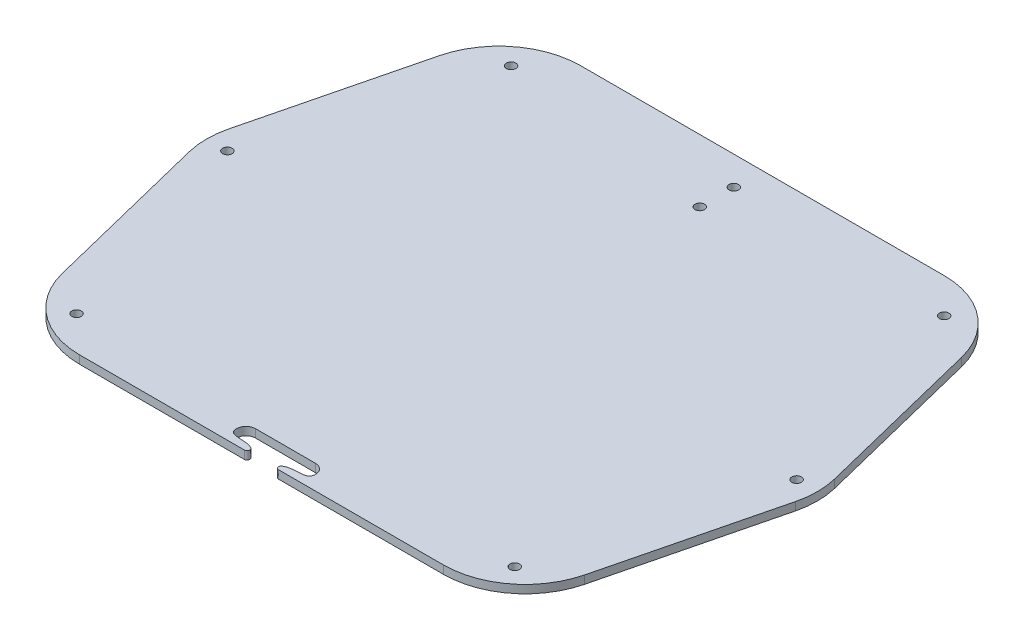
SolidWorks part; units mm, degrees
ref_plane "前视基准面" through (0, 0, 0) normal (0, 0, 1) x (1, 0, 0)
ref_plane "上视基准面" through (0, 0, 0) normal (0, 1, 0) x (1, 0, 0)
ref_plane "右视基准面" through (0, 0, 0) normal (1, 0, 0) x (0, 0, -1)
sketch "草图1" plane through (0, 0, 0) normal (0, 1, 0) x (1, 0, 0)
  line L3 (-66.7806, 154.594) -> (66.7806, 154.594)
  line L4 (-95.8987, 131.8145) -> (-111.2655, 69.8447)
  line L5 (-96.25, 148.3486) -> (-96.25, 83.3486) construction
  line L6 (95.8987, 131.8145) -> (111.2655, 69.8447)
  line L7 (95.8987, -6.5662) -> (111.2655, 55.4037)
  line L9 (-95.8987, -6.5662) -> (-111.2655, 55.4037)
  line L10 (137.9048, 62.6242) -> (-113.2043, 62.6242) construction
  line L12 (-66.7806, -29.3457) -> (66.7806, -29.3457)
  line L20 (0, 9.3997) -> (0, 129.3997) construction
  arc A0 (95.8987, -6.5662) -> (66.7806, -29.3457) centre (66.7806, 0.6543) cw
  arc A1 (-66.7806, -29.3457) -> (-95.8987, -6.5662) centre (-66.7806, 0.6543) cw
  arc A2 (111.2655, 55.4037) -> (111.2655, 69.8447) centre (82.1474, 62.6242) ccw
  arc A3 (-111.2655, 69.8447) -> (-111.2655, 55.4037) centre (-82.1474, 62.6242) ccw
  arc A6 (-66.7806, 154.594) -> (-95.8987, 131.8145) centre (-66.7806, 124.594) ccw
  arc A7 (95.8987, 131.8145) -> (66.7806, 154.594) centre (66.7806, 124.594) ccw
  point P16 (-90.25, 154.594)
  point P18 (90.25, -29.3457)
  point P24 (-90.25, -29.3457)
  point P26 (0, 62.6242)
  point P27 (90.25, 154.594)
  point P28 (113.2043, 62.6242)
  dimension "D5" = 30
  dimension "D6" = 30
extrude "凸台-拉伸1" add sketch "草图1" along normal blind 3
sketch "草图2" plane through (0, 3, 0) normal (0, 1, 0) x (1, 0, 0)
  circle A0 centre (-104.5075, 62.6242) radius 1.75 construction
  circle A1 centre (-80.4502, -16.819) radius 1.75 construction
  circle A2 centre (-104.5075, 62.6242) radius 1.75
  circle A3 centre (-80.4502, -16.819) radius 1.75
  circle A4 centre (104.5075, 62.6242) radius 1.75 construction
  circle A5 centre (80.4502, -16.819) radius 1.75 construction
  circle A6 centre (104.5075, 62.6242) radius 1.75
  circle A7 centre (80.4502, -16.819) radius 1.75
extrude "切除-拉伸1" cut sketch "草图2" against normal blind 10
sketch "草图3" plane through (0, 3, 0) normal (0, 1, 0) x (1, 0, 0)
  circle A0 centre (0, 131.5682) radius 1.75 construction
  circle A1 centre (0, 144.0797) radius 1.75 construction
  circle A2 centre (0, 131.5682) radius 1.75
  circle A3 centre (0, 144.0797) radius 1.75
extrude "切除-拉伸2" cut sketch "草图3" against normal blind 10
sketch "草图4" plane through (0, 3, 0) normal (0, 1, 0) x (1, 0, 0)
  circle A0 centre (-79.5, 141.7823) radius 1.75 construction
  circle A1 centre (79.5, 141.7823) radius 1.75 construction
  circle A2 centre (-79.5, 141.7823) radius 1.75
  circle A3 centre (79.5, 141.7823) radius 1.75
extrude "切除-拉伸3" cut sketch "草图4" against normal blind 10
sketch "草图5" plane through (0, 3, 0) normal (0, 1, 0) x (1, 0, 0)
  line L0 (11.0166, -20.5139) -> (-11.0166, -20.5139) construction
  line L1 (11.0166, -20.5139) -> (-11.0166, -20.5139)
  line L2 (-6.2934, -29.3457) -> (6.2934, -29.3457)
  arc A0 (14.3785, -24.9877) -> (11.0166, -20.5139) centre (11.0166, -24.0139) ccw construction
  arc A1 (5.8046, -27.4733) -> (6.2934, -29.3457) centre (6.2934, -28.3457) ccw construction
  arc A2 (-6.2934, -29.3457) -> (-5.8046, -27.4733) centre (-6.2934, -28.3457) ccw construction
  arc A3 (-11.0166, -20.5139) -> (-14.3785, -24.9877) centre (-11.0166, -24.0139) ccw construction
  arc A4 (-11.0166, -20.5139) -> (-14.3785, -24.9877) centre (-11.0166, -24.0139) ccw
  arc A5 (-6.2934, -29.3457) -> (-5.8046, -27.4733) centre (-6.2934, -28.3457) ccw
  arc A6 (5.8046, -27.4733) -> (6.2934, -29.3457) centre (6.2934, -28.3457) ccw
  arc A7 (14.3785, -24.9877) -> (11.0166, -20.5139) centre (11.0166, -24.0139) ccw
  spline S0 degree 3 poles (2760.8348, 1159.3656) (-7.2239, -47.3403) (1.4545, -25.8897) (22.3045, -27.8983) (63.8711, -2.609) (-2373.261, 1790.5881) knots -1.763167 -1.763167 -1.763167 -1.763167 0.031904 0.50327 4.099766 4.099766 4.099766 4.099766 only from (5.8046, -27.4733) to (14.3785, -24.9877) construction
  spline S1 degree 3 poles (2373.2568, 1790.5851) (-63.8711, -2.6091) (-22.3045, -27.8983) (-1.4545, -25.8897) (7.2239, -47.3402) (-2760.8232, 1159.3606) knots -3.32237 -3.32237 -3.32237 -3.32237 0.274124 0.74549 2.540558 2.540558 2.540558 2.540558 only from (-14.3785, -24.9877) to (-5.8046, -27.4733) construction
  spline S2 degree 3 poles (-14.3785, -24.9877) (-14.0507, -26.1193) (-10.4893, -26.7601) (-7.7247, -26.4938) (-5.9045, -27.4173) (-5.8046, -27.4733) knots 0 0 0 0 0.274124 0.74549 0.777394 0.777394 0.777394 0.777394
  spline S3 degree 3 poles (5.8046, -27.4733) (5.9045, -27.4173) (7.7247, -26.4938) (10.4893, -26.7601) (14.0507, -26.1193) (14.3785, -24.9877) knots 0 0 0 0 0.031904 0.50327 0.777394 0.777394 0.777394 0.777394
extrude "切除-拉伸4" cut sketch "草图5" against normal blind 10
